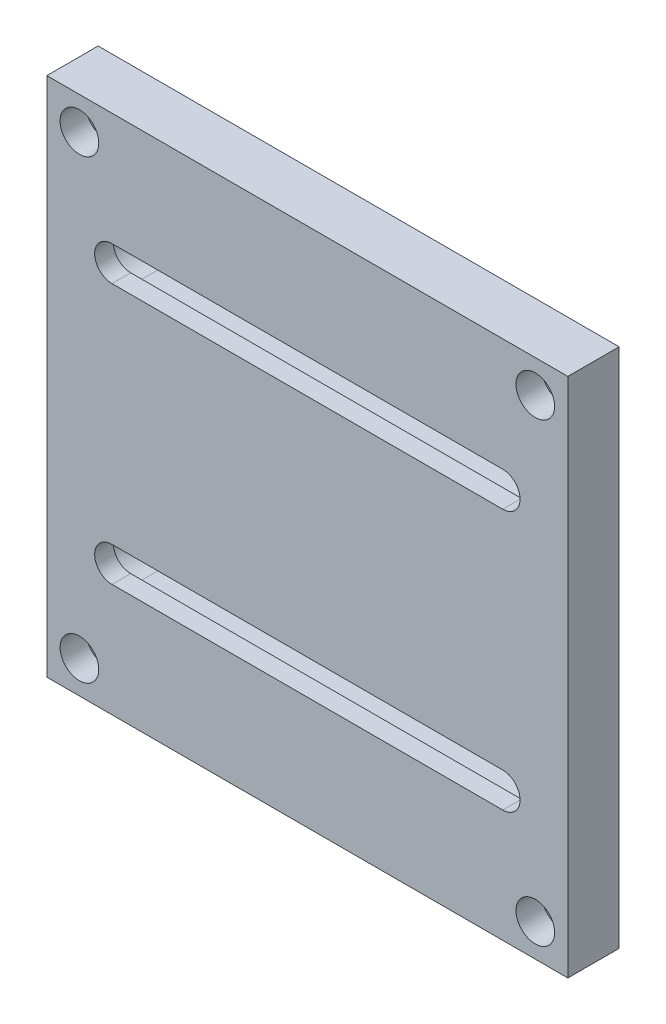
SolidWorks part; units mm, degrees
ref_plane "Front Plane" through (0, 0, 0) normal (0, 0, 1) x (1, 0, 0)
ref_plane "Top Plane" through (0, 0, 0) normal (0, 1, 0) x (1, 0, 0)
ref_plane "Right Plane" through (0, 0, 0) normal (1, 0, 0) x (0, 0, -1)
sketch "Sketch1" plane through (0, 0, 0) normal (0, 0, 1) x (1, 0, 0)
  line L1 (6.35, 6.35) -> (-95.25, 6.35)
  line L2 (6.35, 6.35) -> (6.35, -95.25)
  line L3 (6.35, -95.25) -> (-95.25, -95.25)
  line L4 (-95.25, 6.35) -> (-95.25, -95.25)
extrude "Boss-Extrude1" add sketch "Sketch1" along normal blind 10
hole_wizard "CBORE for #6 Button Head Cap Screw1" positions "Sketch2" profile "Sketch4" counterbore size "#6" standard "ANSI Inch" end condition through all
sketch "Sketch2" plane through (0, 0, 10) normal (0, 0, 1) x (1, 0, 0)
  point P0 (0, 0)
  point P3 (0, -88.9)
  point P6 (-88.9, -88.9)
  point P9 (-88.9, 0)
sketch "Sketch4" plane through (0, 0, 10) normal (1, 0, 0) x (0, -1, 0)
  line L0 (0, 0) -> (0, 10)
  line L1 (0, 10) -> (1.8986, 10)
  line L3 (1.8986, 10) -> (1.8986, 5.08)
  line L4 (1.8986, 5.08) -> (3.7706, 5.08)
  line L5 (3.7706, 5.08) -> (3.7706, 0)
  line L7 (3.7706, 0) -> (0, 0)
  line L11 (0, -6.35) -> (0, 107.95) construction
  dimension "Thru Hole Dia." = 3.7973
  dimension "Thru Hole Depth" = 10
  dimension "C'Bore Dia." = 7.5413
  dimension "C'Bore Depth" = 5.08
sketch "Sketch5" plane through (0, 0, 0) normal (0, 0, -1) x (-1, 0, 0)
  line L1 (6.35, -69.85) -> (82.55, -69.85)
  line L2 (6.35, -69.85) -> (6.35, -19.05)
  line L3 (6.35, -19.05) -> (82.55, -19.05)
  line L4 (82.55, -69.85) -> (82.55, -19.05)
  line L5 (6.35, -69.85) -> (82.55, -19.05) construction
  line L6 (6.35, -19.05) -> (82.55, -69.85) construction
  point P0 (44.45, -44.45)
  dimension "D1" = 50.8
  dimension "D2" = 76.2
hole_wizard "CBORE for 1/4 Socket Head Cap Screw1" positions "Sketch6" profile "Sketch7" counterbore size "1/4" standard "ANSI Inch" end condition through all
sketch "Sketch6" plane through (0, 0, 0) normal (0, 0, -1) x (-1, 0, 0)
  point P0 (82.55, -19.05)
  point P3 (82.55, -69.85)
  point P6 (6.35, -69.85)
  point P9 (6.35, -19.05)
sketch "Sketch7" plane through (-82.55, -19.05, 0) normal (1, 0, 0) x (0, 1, 0)
  line L0 (0, 0) -> (0, 10)
  line L1 (0, 10) -> (3.3782, 10)
  line L3 (3.3782, 10) -> (3.3782, 6.35)
  line L4 (3.3782, 6.35) -> (5.5562, 6.35)
  line L5 (5.5562, 6.35) -> (5.5562, 0)
  line L7 (5.5562, 0) -> (0, 0)
  line L11 (0, -6.35) -> (0, 107.95) construction
  dimension "Thru Hole Dia." = 6.7564
  dimension "Thru Hole Depth" = 10
  dimension "C'Bore Dia." = 11.1125
  dimension "C'Bore Depth" = 6.35
sketch "Sketch8" plane through (0, 0, 0) normal (0, 0, -1) x (-1, 0, 0)
  line L0 (6.35, -69.85) -> (6.35, -19.05) construction
  line L1 (82.55, -13.4938) -> (6.35, -13.4938)
  line L2 (82.55, -13.4938) -> (82.55, -24.6063)
  line L3 (82.55, -24.6063) -> (6.35, -24.6063)
  line L4 (6.35, -13.4938) -> (6.35, -24.6063)
  line L5 (82.55, -69.85) -> (82.55, -19.05) construction
  line L6 (6.35, -75.4063) -> (82.55, -75.4063)
  line L7 (6.35, -75.4063) -> (6.35, -64.2938)
  line L8 (6.35, -64.2938) -> (82.55, -64.2938)
  line L9 (82.55, -75.4063) -> (82.55, -64.2938)
  circle A0 centre (82.55, -19.05) radius 5.5562 construction
  circle A1 centre (6.35, -19.05) radius 5.5562 construction
  circle A2 centre (6.35, -69.85) radius 5.5562 construction
  circle A3 centre (82.55, -69.85) radius 5.5562 construction
extrude "Cut-Extrude1" cut sketch "Sketch8" against normal up to surface (6.35 mm away) up to face at (-85.9282, -19.05, 6.35)
sketch "Sketch10" plane through (0, 0, 6.35) normal (0, 0, -1) x (-1, 0, 0)
  line L1 (82.55, -15.6718) -> (6.35, -15.6718)
  line L2 (82.55, -15.6718) -> (82.55, -22.4282)
  line L3 (82.55, -22.4282) -> (6.35, -22.4282)
  line L4 (6.35, -15.6718) -> (6.35, -22.4282)
  line L5 (6.35, -66.4718) -> (82.55, -66.4718)
  line L6 (6.35, -66.4718) -> (6.35, -73.2282)
  line L7 (6.35, -73.2282) -> (82.55, -73.2282)
  line L8 (82.55, -66.4718) -> (82.55, -73.2282)
  circle A0 centre (82.55, -19.05) radius 3.3782 construction
  circle A1 centre (6.35, -19.05) radius 3.3782 construction
  circle A2 centre (6.35, -69.85) radius 3.3782 construction
  circle A3 centre (82.55, -69.85) radius 3.3782 construction
extrude "Cut-Extrude2" cut sketch "Sketch10" against normal through all
